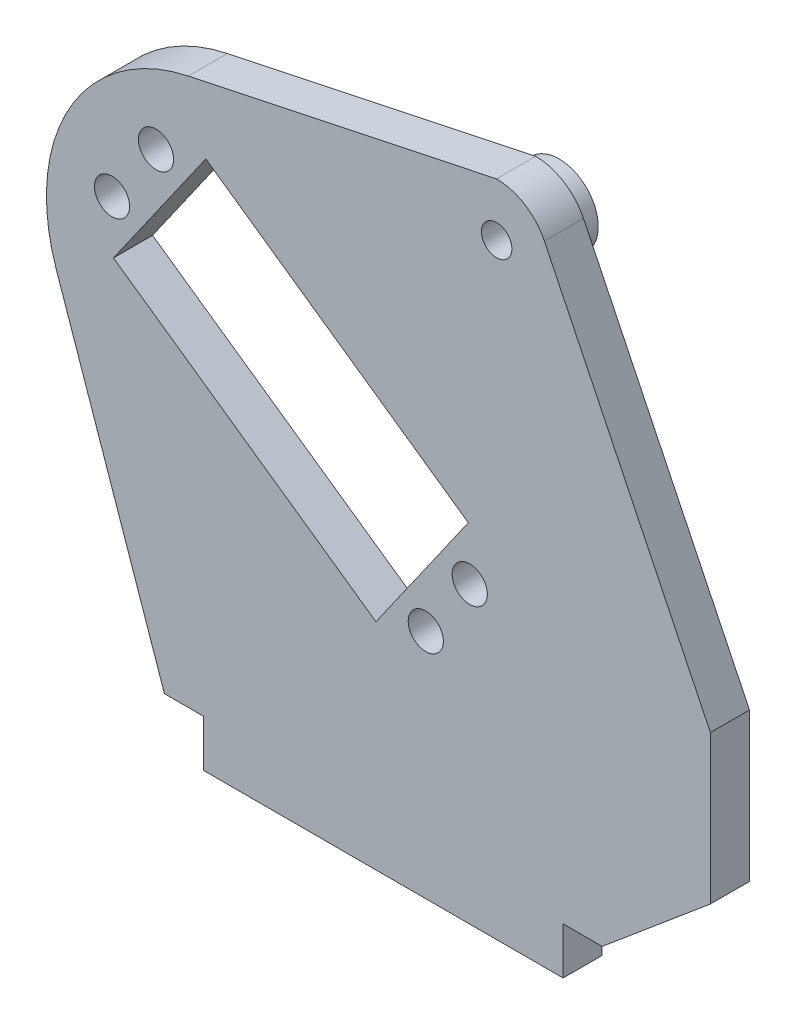
SolidWorks part; units mm, degrees
ref_plane "Front Plane" through (0, 0, 0) normal (0, 0, 1) x (1, 0, 0)
ref_plane "Top Plane" through (0, 0, 0) normal (0, 1, 0) x (1, 0, 0)
ref_plane "Right Plane" through (0, 0, 0) normal (1, 0, 0) x (0, 0, -1)
sketch "Sketch1" plane through (0, 0, 0) normal (0, 0, 1) x (1, 0, 0)
  line L1 (41.85, 40.6215) -> (20.6106, 84.4605) construction
  line L2 (41.85, 21.6215) -> (41.85, 40.6215) construction
  line L3 (28, 10) -> (41.85, 21.6215) construction
  line L4 (-28, 10) -> (-41.8438, 50.1182) construction
  line L5 (-23, 10) -> (-28, 10) construction
  line L6 (-23, 10) -> (-23, 0) construction
  line L7 (23, 0) -> (23, 10) construction
  line L8 (-29.0824, 69.7673) -> (-34.7034, 61.7396) construction
  line L10 (41.85, 40.6215) -> (20.6106, 84.4605)
  line L11 (41.85, 21.6215) -> (41.85, 40.6215)
  line L12 (28, 10) -> (41.85, 21.6215)
  line L13 (-28, 10) -> (-41.8438, 50.1182)
  line L14 (-23, 10) -> (-28, 10)
  line L15 (-23, 10) -> (-23, 4)
  line L16 (23, 4) -> (23, 10)
  line L18 (28, 10) -> (23, 10)
  line L19 (0, 0) -> (0, 7.7981) construction
  line L20 (-22.7085, 71.8964) -> (-34.5241, 55.0219)
  line L21 (-22.7085, 71.8964) -> (10.8768, 48.3798)
  line L22 (-34.5241, 55.0219) -> (-0.9389, 31.5053)
  line L23 (10.8768, 48.3798) -> (-0.9389, 31.5053)
  line L24 (4.9689, 39.9425) -> (-28.6163, 63.4592) construction
  line L25 (-11.8237, 51.7008) -> (-17.7315, 43.2636) construction
  line L30 (-24.9456, 79.9616) -> (14.5, 88.29)
  line L31 (-23, 4) -> (23, 4)
  arc A0 (-20.22, 80.455) -> (-41.8438, 50.1182) centre (-20.22, 57.58) ccw construction
  arc A1 (20.6106, 84.4605) -> (14.5, 88.29) centre (14.5, 81.5) ccw construction
  arc A2 (-24.9456, 79.9616) -> (-41.8438, 50.1182) centre (-20.22, 57.58) ccw
  arc A3 (20.6106, 84.4605) -> (14.5, 88.29) centre (14.5, 81.5) ccw
  circle A7 centre (-29.0824, 69.7673) radius 2.25
  circle A8 centre (-34.7034, 61.7396) radius 2.25
  circle A9 centre (5.435, 33.6344) radius 2.25
  circle A10 centre (11.0561, 41.6621) radius 2.25
  point P0 (28, 10)
  point P17 (14.5, 81.5)
  point P28 (-20.22, 57.58)
  point P38 (-31.8929, 65.7535)
  dimension "D9" = 4
  dimension "D8" = 4.5
  dimension "D2" = 6
  dimension "D4" = 41
  dimension "D5" = 20.6
  dimension "D6" = 9.8
  dimension "D7" = 10.25
extrude "Boss-Extrude1" add sketch "Sketch1" against normal blind 5
hole_wizard "M3.5 Clearance Hole1" positions "Sketch8" profile "Sketch9" hole size "M3.5" standard "ISO"
sketch "Sketch8" plane through (0, 0, 0) normal (0, 0, 1) x (1, 0, 0)
  point P0 (14.5, 81.5)
sketch "Sketch9" plane through (14.5, 81.5, 0) normal (1, 0, 0) x (0, -1, 0)
  line L0 (0, 0) -> (0, 11.1717)
  line L1 (0, 11.1717) -> (1.95, 10)
  line L2 (1.95, 10) -> (1.95, 0)
  line L5 (1.95, 0) -> (0, 0)
  line L10 (0, 11.1717) -> (-1.95, 10) construction
  line L11 (0, -6.35) -> (0, 107.95) construction
  dimension "Hole Dia." = 3.9
  dimension "Hole Depth" = 10
  dimension "Drill Angle" = 118
sketch "草图2" plane through (0, 0, -5) normal (0, 0, -1) x (-1, 0, 0)
  circle A0 centre (-14.5, 81.5) radius 5
  circle A1 centre (-14.5, 81.5) radius 1.95
  dimension "D1" = 10
extrude "凸台-拉伸2" add sketch "草图2" along normal blind 3
